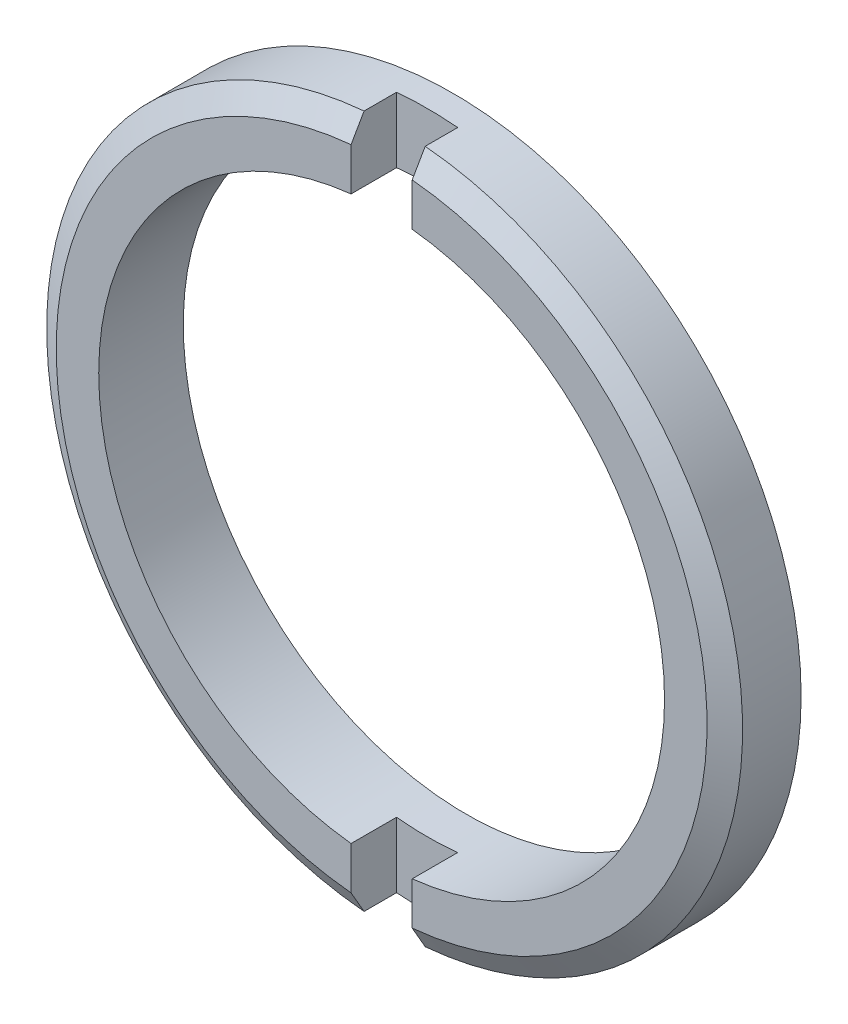
SolidWorks part; units mm, degrees
material "6061 Alloy"
ref_plane "Front Plane" through (0, 0, 0) normal (0, 0, 1) x (1, 0, 0)
ref_plane "Top Plane" through (0, 0, 0) normal (0, 1, 0) x (1, 0, 0)
ref_plane "Right Plane" through (0, 0, 0) normal (1, 0, 0) x (0, 0, -1)
sketch "Sketch1" plane through (0, 0, 0) normal (0, 0, 1) x (1, 0, 0)
  circle A0 centre (0, 0) radius 5.5245
  circle A1 centre (0, 0) radius 6.7945
  dimension "D1" = 11.049
  dimension "D2" = 13.589
extrude "Extrude1" add sketch "Sketch1" along normal mid plane 1.651
sketch "Sketch2" plane through (0, 0, 0.8255) normal (0, 0, 1) x (1, 0, 0)
  line L0 (0, 5.5245) -> (0, 6.7945) construction
  line L1 (-0.5969, 6.7682) -> (-0.5969, 5.4922)
  line L2 (0.5969, 6.7682) -> (0.5969, 5.4922)
  line L3 (-6.7945, 0) -> (6.7945, 0) construction
  line L4 (0, -5.5245) -> (0, -6.7945) construction
  line L5 (-0.5969, -6.7682) -> (-0.5969, -5.4922)
  line L6 (0.5969, -6.7682) -> (0.5969, -5.4922)
  circle A0 centre (0, 0) radius 5.5245 construction
  circle A1 centre (0, 0) radius 6.7945 construction
  arc A2 (-0.5969, -5.4922) -> (0.5969, -5.4922) centre (0, 0) ccw
  arc A3 (-0.5969, -6.7682) -> (0.5969, -6.7682) centre (0, 0) ccw
  arc A4 (0.5969, 5.4922) -> (-0.5969, 5.4922) centre (0, 0) ccw
  arc A5 (0.5969, 6.7682) -> (-0.5969, 6.7682) centre (0, 0) ccw
  dimension "D1" = 1.1938
extrude "Cut-Extrude1" cut sketch "Sketch2" against normal blind 0.889
chamfer "Chamfer1" distance 0.254 angle 60 3 edges at (6.7945, 0, -0.8255) (-6.7945, 0, 0.8255) (6.7945, 0, 0.8255)
